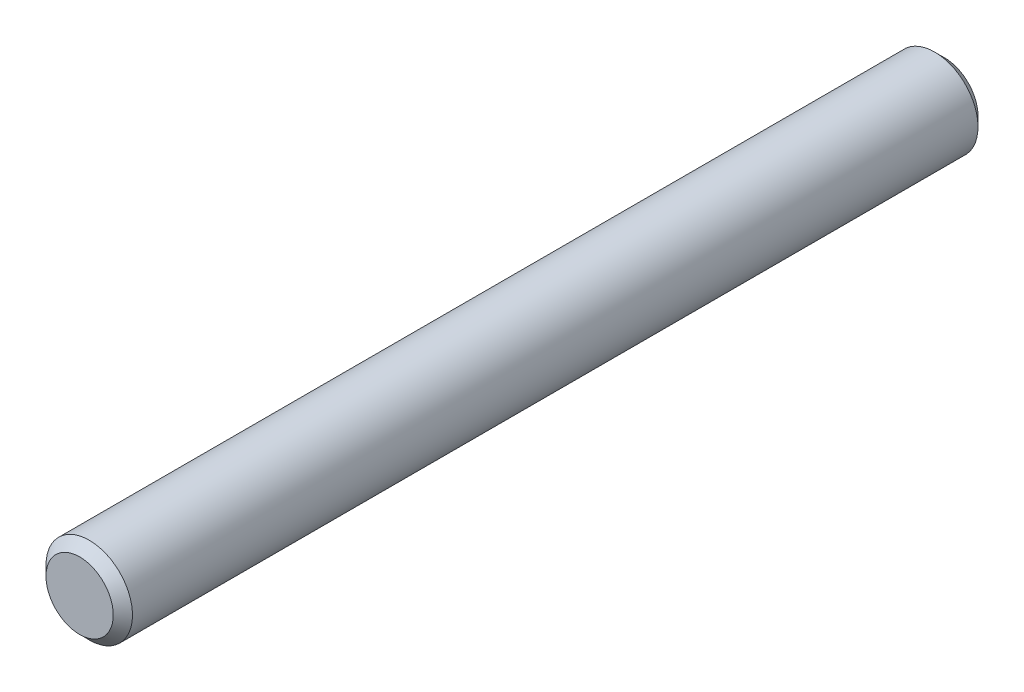
SolidWorks part; units mm, degrees
ref_plane "Piano frontale" through (0, 0, 0) normal (0, 0, 1) x (1, 0, 0)
ref_plane "Piano superiore" through (0, 0, 0) normal (0, 1, 0) x (1, 0, 0)
ref_plane "Piano destro" through (0, 0, 0) normal (1, 0, 0) x (0, 0, -1)
sketch "Schizzo1" plane through (0, 0, 0) normal (0, 0, 1) x (1, 0, 0)
  circle A0 centre (0, 0) radius 2.25
  dimension "D1" = 4.5
extrude "Estrusione-Estrusione1" add sketch "Schizzo1" along normal blind 45
chamfer "Smusso1" distance 0.5 angle 45 2 edges at (2.25, 0, 0) (2.25, 0, 45)
